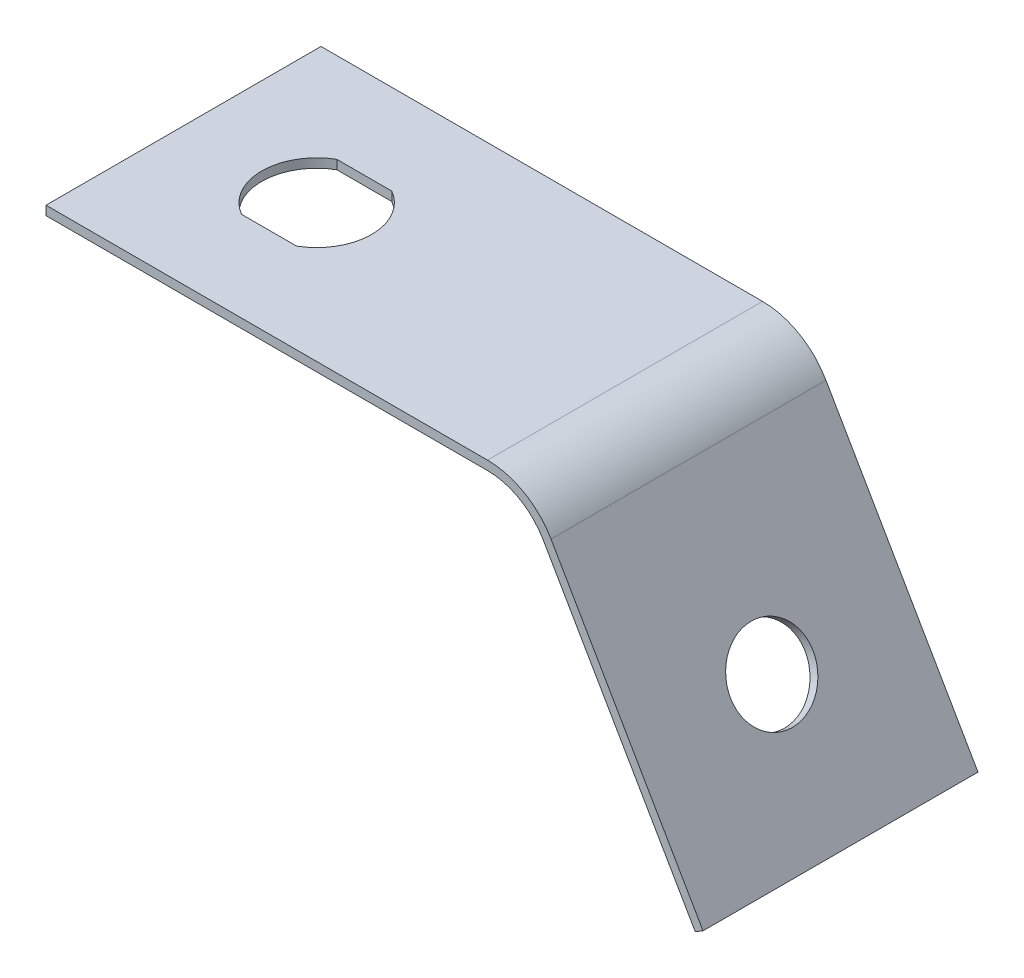
SolidWorks part; units mm, degrees
ref_plane "Front Plane" through (0, 0, 0) normal (0, 0, 1) x (1, 0, 0)
ref_plane "Top Plane" through (0, 0, 0) normal (0, 1, 0) x (1, 0, 0)
ref_plane "Right Plane" through (0, 0, 0) normal (1, 0, 0) x (0, 0, -1)
sketch "Sketch1" plane through (0, 0, 0) normal (0, 0, 1) x (1, 0, 0)
  line L0 (-44.45, 0) -> (-3.6662, 0)
  line L1 (1.8331, -3.175) -> (15.875, -27.4963)
  arc A0 (-3.6662, 0) -> (1.8331, -3.175) centre (-3.6662, -6.35) cw
  point P5 (0, 0)
  dimension "D4" = 6.35
  dimension "D1" = 31.75
  dimension "D2" = 120
  dimension "D3" = 44.45
extrude "Extrude-Thin1" add sketch "Sketch1" along normal mid plane 25.4 thin thin type mid plane wall 0.8382
sketch "Sketch2" plane through (0, 0.4191, 0) normal (0, 1, 0) x (1, 0, 0)
  line L0 (-34.6891, 4.3994) -> (-29.6091, 4.3994)
  line L1 (-29.6091, -4.3994) -> (-34.6891, -4.3994)
  line L2 (-44.45, -12.7) -> (-3.6662, -12.7) construction
  line L3 (-44.45, -12.7) -> (-44.45, 12.7) construction
  arc A0 (-29.6091, -4.3994) -> (-29.6091, 4.3994) centre (-32.1491, 0) ccw
  arc A1 (-34.6891, 4.3994) -> (-34.6891, -4.3994) centre (-32.1491, 0) ccw
  dimension "D4" = 5.08
  dimension "D1" = 12.7
  dimension "D2" = 12.3009
  dimension "D3" = 5.08
extrude "Cut-Extrude1" cut sketch "Sketch2" against normal through all
sketch "Sketch3" plane through (-0.363, -0.2096, 0) normal (-0.866, -0.5, 0) x (0, 0, 1)
  line L0 (12.7, -31.75) -> (-12.7, -31.75) construction
  circle A0 centre (0, -19.05) radius 3.81
  point P7 (0, -31.75)
  dimension "D2" = 7.62
  dimension "D1" = 12.7
extrude "Cut-Extrude2" cut sketch "Sketch3" against normal through all
